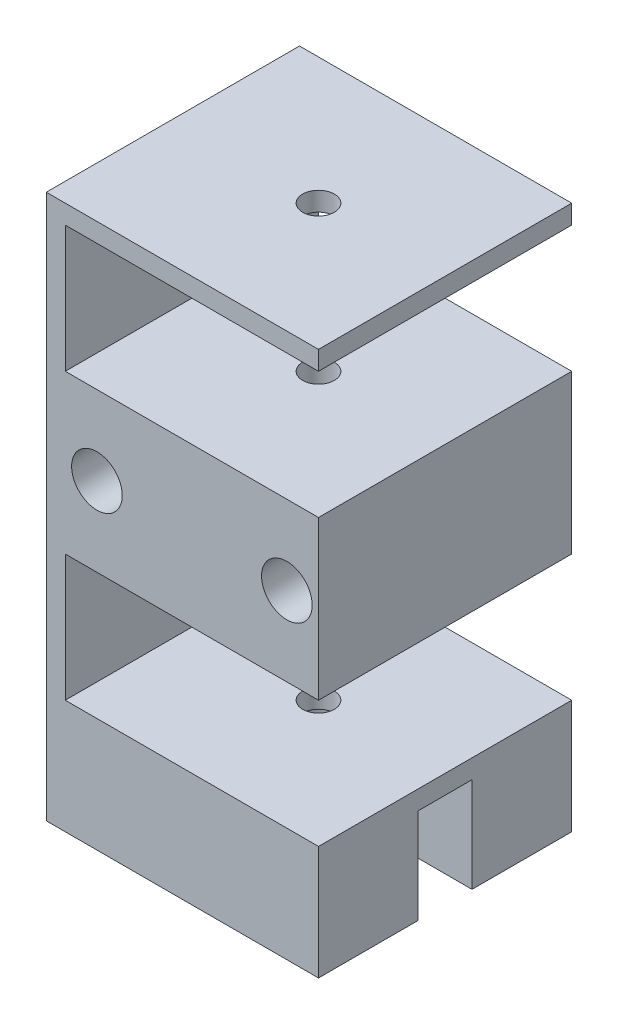
SolidWorks part; units mm, degrees
ref_plane "Front Plane" through (0, 0, 0) normal (0, 0, 1) x (1, 0, 0)
ref_plane "Top Plane" through (0, 0, 0) normal (0, 1, 0) x (1, 0, 0)
ref_plane "Right Plane" through (0, 0, 0) normal (1, 0, 0) x (0, 0, -1)
sketch "Sketch1" plane through (0, 0, 0) normal (0, 0, 1) x (1, 0, 0)
  line L0 (0, 0) -> (-40, 0)
  line L1 (-40, 0) -> (-40, 20)
  line L2 (-40, 20) -> (0, 20)
  line L3 (0, 20) -> (0, 45)
  line L4 (0, 68) -> (-43, 68)
  line L5 (0, 0) -> (0, -18)
  line L6 (0, -18) -> (-43, -18)
  line L7 (-43, 45) -> (-43, -18)
  line L8 (0, 45) -> (-40, 45)
  line L9 (-43, 45) -> (-43, 65)
  line L10 (-40, 45) -> (-40, 65)
  line L11 (-43, 65) -> (-43, 68)
  line L12 (-40, 65) -> (0, 65)
  line L13 (0, 65) -> (0, 68)
  line L14 (0, 32.5) -> (-5, 32.5) construction
  line L15 (-5, 32.5) -> (-35, 32.5) construction
  line L16 (-35, 32.5) -> (-40, 32.5) construction
  line L17 (-40, 32.5) -> (-40, 20) construction
  circle A0 centre (-35, 32.5) radius 4
  circle A1 centre (-5, 32.5) radius 4
  dimension "D11" = 8
  dimension "D12" = 8
  dimension "D1" = 20
  dimension "D2" = 40
  dimension "D3" = 40
  dimension "D4" = 3
  dimension "D5" = 3
  dimension "D6" = 20
  dimension "D7" = 3
  dimension "D8" = 18
  dimension "D9" = 25
  dimension "D10" = 30
extrude "Boss-Extrude1" add sketch "Sketch1" along normal blind 40
sketch "Sketch3" plane through (0, 20, 0) normal (0, -1, 0) x (-1, 0, 0)
  line L0 (40, -40) -> (0, 0) construction
  circle A0 centre (20, -20) radius 2.5
  dimension "D1" = 5
extrude "Cut-Extrude1" cut sketch "Sketch3" against normal through all both and the other way through all
sketch "Sketch4" plane through (0, -18, 0) normal (0, -1, 0) x (-1, 0, 0)
  line L0 (20, -24.25) -> (0, -24.25)
  line L1 (0, -40) -> (0, 0) construction
  line L2 (0, -24.25) -> (0, -15.75)
  line L3 (0, -15.75) -> (20, -15.75)
  arc A0 (20, -24.25) -> (20, -15.75) centre (20, -20) ccw
  dimension "D1" = 8.5
extrude "Cut-Extrude2" cut sketch "Sketch4" against normal blind 15
